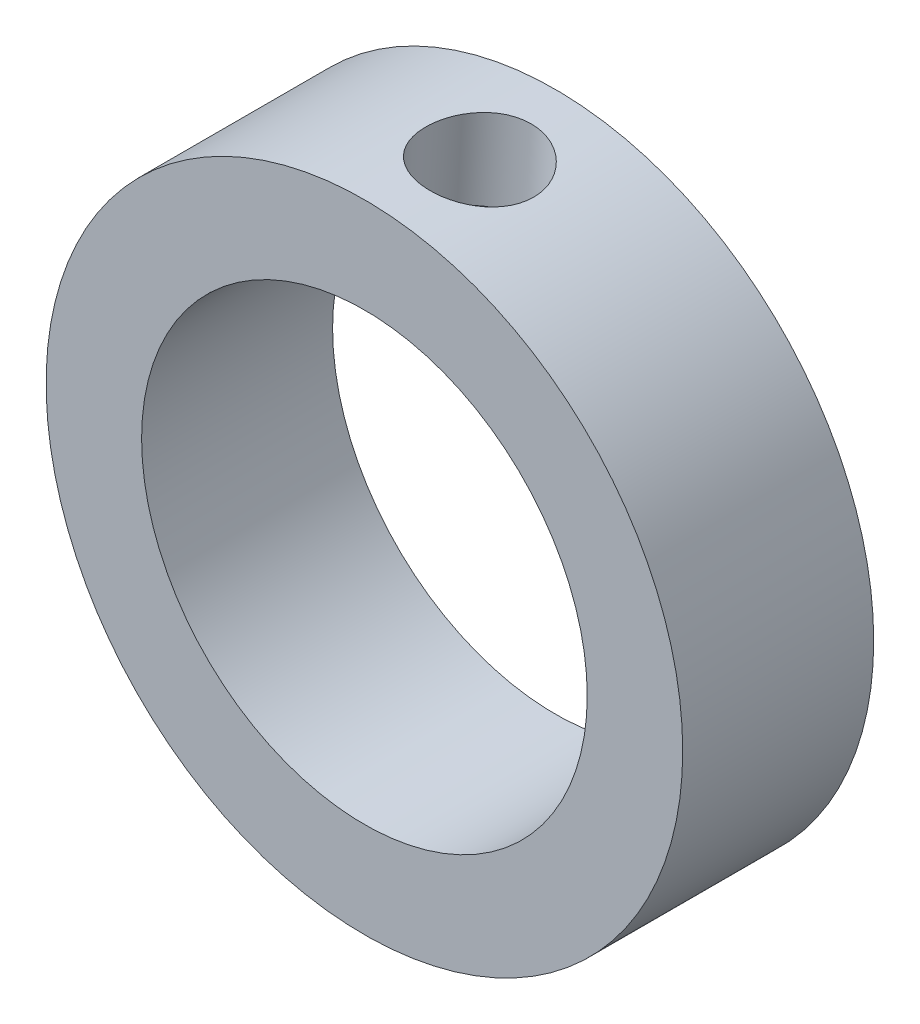
SolidWorks part; units mm, degrees
material "СТ3КП"
ref_plane "Спереди" through (0, 0, 0) normal (0, 0, 1) x (1, 0, 0)
ref_plane "Сверху" through (0, 0, 0) normal (0, 1, 0) x (1, 0, 0)
ref_plane "Справа" through (0, 0, 0) normal (1, 0, 0) x (0, 0, -1)
sketch "Эскиз1" plane through (0, 0, 0) normal (0, 0, 1) x (1, 0, 0)
  circle A0 centre (0, 0) radius 17.5
  circle A1 centre (0, 0) radius 25
  dimension "D1" = 35
  dimension "D2" = 50
extrude "Бобышка-Вытянуть1" add sketch "Эскиз1" along normal blind 15
hole_wizard "Отверстие обработанное метчиком M102" positions "Трехмерный эскиз1" profile "Эскиз4" tap size "M10" standard "ISO"
sketch3d "Трехмерный эскиз1"
  line L0 (1.1064, 17.465, 15) -> (1.1064, 17.465, 0) construction
  circle A0 centre (0, 0, 15) radius 17.5 construction
  circle A1 centre (0, 0, 0) radius 17.5 construction
  point P0 (1.1064, 17.465, 7.5)
  point P7 (0, 0, 32.5)
  point P10 (0, 0, 17.5)
  point P13 (1.1064, 17.465, 7.5)
cosmetic thread "Отверстие резьбы2" parameters "D1"=30, "D2"=10
sketch "Эскиз4" plane through (1.1064, 17.465, 7.5) normal (0, 0, 1) x (0.998, -0.0632, 0)
  line L0 (0, 0) -> (0, 27.5)
  line L1 (0, 27.5) -> (4.25, 24.9463)
  line L2 (4.25, 24.9463) -> (4.25, 0.775)
  line L3 (4.25, 0.775) -> (5.025, 0)
  line L5 (5.025, 0) -> (0, 0)
  line L6 (-4.25, 0.775) -> (-5.025, 0) construction
  line L10 (0, 27.5) -> (-4.25, 24.9463) construction
  line L11 (0, -6.35) -> (0, 107.95) construction
  dimension "Диаметр сверла" = 8.5
  dimension "Глубина сверла" = 27.5
  dimension "Диаметр передней зенковки" = 10.05
  dimension "Угол передней зенковки" = 90
  dimension "Угол заточки сверла" = 118
cosmetic thread "Условное изображение резьбы1" parameters "D2"=10
